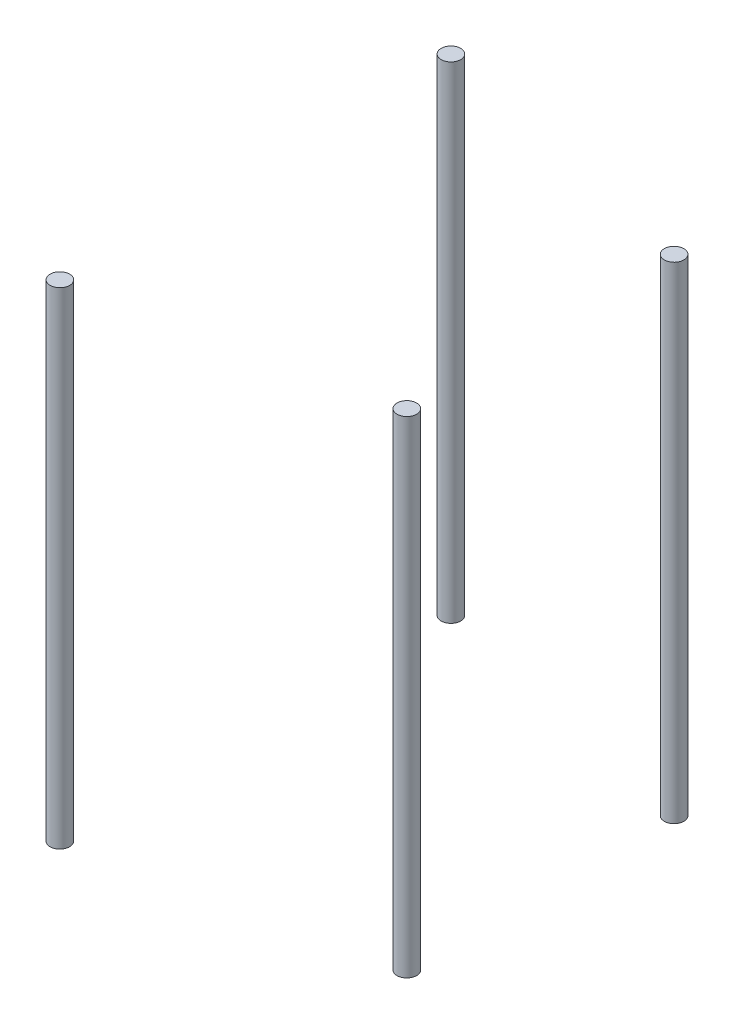
SolidWorks part; units mm, degrees
ref_plane "Front Plane" through (0, 0, 0) normal (0, 0, 1) x (1, 0, 0)
ref_plane "Top Plane" through (0, 0, 0) normal (0, 1, 0) x (1, 0, 0)
ref_plane "Right Plane" through (0, 0, 0) normal (1, 0, 0) x (0, 0, -1)
sketch "Sketch2" plane through (0.0002, 96.488, 0) normal (0, 1, 0) x (1, 0, 0)
  line L2 (0, 0) -> (103.9681, 0) construction
  circle A0 centre (-57.0586, -120.0342) radius 6
  circle A1 centre (117.9643, -82.0443) radius 6
  arc A2 (-56.0586, -121.7663) -> (-56.0586, -118.3022) centre (-57.0586, -120.0342) ccw construction
  circle A3 centre (117.9643, -82.0443) radius 2 construction
  circle A4 centre (117.9643, 82.0443) radius 6
  circle A5 centre (-57.0586, 120.0342) radius 6
  dimension "D1" = 12
  dimension "D2" = 12
extrude "Boss-Extrude2" add sketch "Sketch2" along normal up to surface (298.5119 mm away)
equation "\"D2@Sketch2\"=\"D1@Sketch2\""
